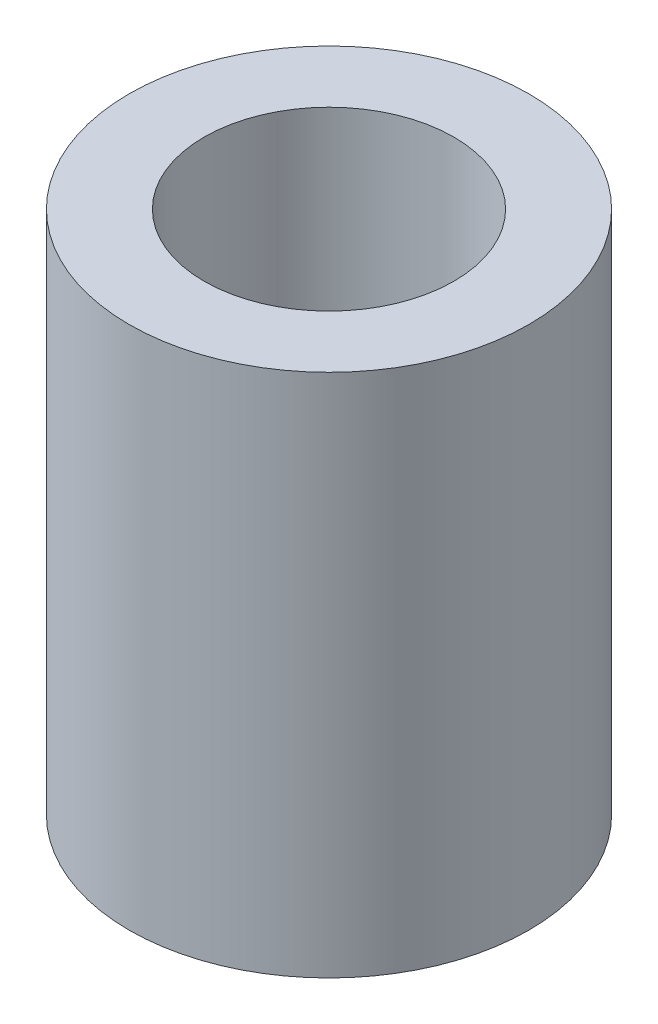
SolidWorks part; units mm, degrees
ref_plane "前视基准面" through (0, 0, 0) normal (0, 0, 1) x (1, 0, 0)
ref_plane "上视基准面" through (0, 0, 0) normal (0, 1, 0) x (1, 0, 0)
ref_plane "右视基准面" through (0, 0, 0) normal (1, 0, 0) x (0, 0, -1)
sketch "草图1" plane through (0, 0, 0) normal (0, 1, 0) x (1, 0, 0)
  circle A0 centre (0, 0) radius 16
  circle A1 centre (0, 0) radius 10
  dimension "D1" = 32
extrude "拉伸1" add sketch "草图1" along normal blind 42
